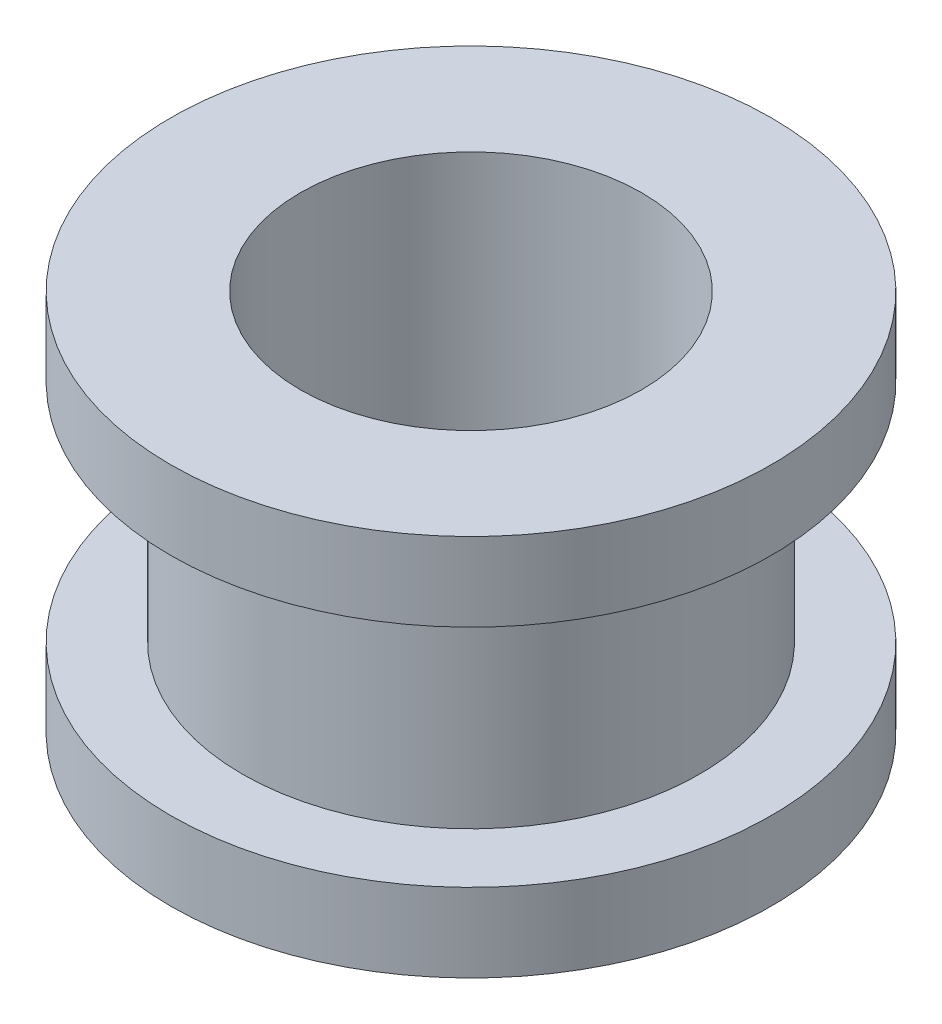
SolidWorks part; units mm, degrees
material "Rubber"
ref_plane "Front Plane" through (0, 0, 0) normal (0, 0, 1) x (1, 0, 0)
ref_plane "Top Plane" through (0, 0, 0) normal (0, 1, 0) x (1, 0, 0)
ref_plane "Right Plane" through (0, 0, 0) normal (1, 0, 0) x (0, 0, -1)
sketch "Sketch1" plane through (0, 0, 0) normal (0, 0, 1) x (1, 0, 0)
  line L0 (0, 5.6) -> (-8.8, 5.6)
  line L1 (0, -55) -> (0, 55) construction
  line L2 (-8.8, 5.6) -> (-8.8, 3.3)
  line L3 (-8.8, 3.3) -> (-6.7, 3.3)
  line L4 (-6.7, 3.3) -> (-6.7, -3.3)
  line L5 (-6.7, -3.3) -> (-8.8, -3.3)
  line L6 (-8.8, -3.3) -> (-8.8, -5.6)
  line L7 (-8.8, -5.6) -> (0, -5.6)
  line L8 (0, -5.6) -> (0, 5.6)
  line L9 (55, 0) -> (-55, 0) construction
  point P12 (0, 0)
  dimension "D1" = 11.2
  dimension "D2" = 8.8
  dimension "D3" = 6.7
  dimension "D4" = 6.6
revolve "Revolve1" add sketch "Sketch1" angle 360 about L8
sketch "Sketch2" plane through (0, 0, 0) normal (0, 1, 0) x (1, 0, 0)
  circle A0 centre (0, 0) radius 5
  dimension "D1" = 10
extrude "Cut-Extrude1" cut sketch "Sketch2" against normal through all both and the other way through all
